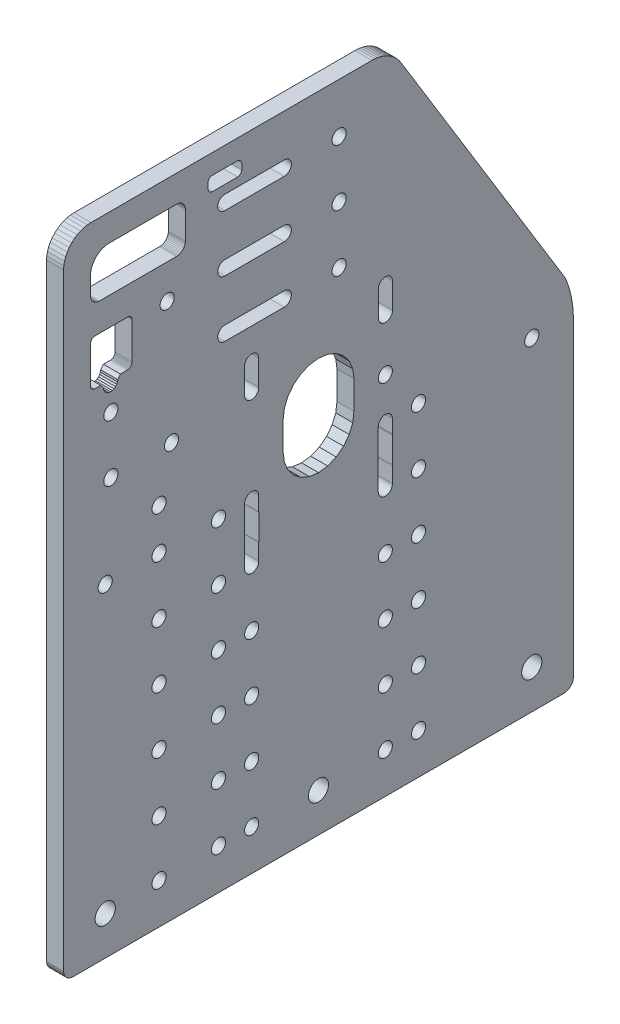
SolidWorks part; units mm, degrees
ref_plane "Front Plane" through (0, 0, 0) normal (0, 0, 1) x (1, 0, 0)
ref_plane "Top Plane" through (0, 0, 0) normal (0, 1, 0) x (1, 0, 0)
ref_plane "Right Plane" through (0, 0, 0) normal (1, 0, 0) x (0, 0, -1)
ref_plane "Plane1" through (0, 0, 0) normal (-1, 0, 0) x (0, -1, 0)
sketch "Sketch1" plane through (0, 0, 0) normal (-1, 0, 0) x (0, -1, 0)
  line L0 (-590.2121, -1614.2437) -> (-495.2304, -1672.3356)
  line L1 (-495.2304, -1672.3356) -> (-492.9855, -1673.1988)
  line L2 (-492.9855, -1673.1988) -> (-490.6881, -1673.9103)
  line L3 (-490.6881, -1673.9103) -> (-488.3483, -1674.4671)
  line L4 (-488.3483, -1674.4671) -> (-485.9766, -1674.8665)
  line L5 (-485.9766, -1674.8665) -> (-483.5835, -1675.1069)
  line L6 (-483.5835, -1675.1069) -> (-481.1798, -1675.1871)
  line L7 (-481.1798, -1675.1871) -> (-371.8266, -1675.1871)
  line L8 (-371.8266, -1675.1871) -> (-371.3877, -1675.1584)
  line L9 (-371.3877, -1675.1584) -> (-370.9562, -1675.0725)
  line L10 (-370.9562, -1675.0725) -> (-370.5397, -1674.9312)
  line L11 (-370.5397, -1674.9312) -> (-370.1452, -1674.7366)
  line L12 (-370.1452, -1674.7366) -> (-369.7795, -1674.4922)
  line L13 (-369.7795, -1674.4922) -> (-369.4487, -1674.2022)
  line L14 (-369.4487, -1674.2022) -> (-369.1587, -1673.8715)
  line L15 (-369.1587, -1673.8715) -> (-368.9143, -1673.5057)
  line L16 (-368.9143, -1673.5057) -> (-368.7198, -1673.1112)
  line L17 (-368.7198, -1673.1112) -> (-368.5784, -1672.6947)
  line L18 (-368.5784, -1672.6947) -> (-368.4926, -1672.2633)
  line L19 (-368.4926, -1672.2633) -> (-368.4638, -1671.8243)
  line L20 (-368.4638, -1671.8243) -> (-368.4638, -1498.5099)
  line L21 (-368.4638, -1498.5099) -> (-368.4926, -1498.071)
  line L22 (-368.4926, -1498.071) -> (-368.5784, -1497.6396)
  line L23 (-368.5784, -1497.6396) -> (-368.7198, -1497.223)
  line L24 (-368.7198, -1497.223) -> (-368.9143, -1496.8285)
  line L25 (-368.9143, -1496.8285) -> (-369.1587, -1496.4628)
  line L26 (-369.1587, -1496.4628) -> (-369.4487, -1496.1321)
  line L27 (-369.4487, -1496.1321) -> (-369.7795, -1495.842)
  line L28 (-369.7795, -1495.842) -> (-370.1452, -1495.5977)
  line L29 (-370.1452, -1495.5977) -> (-370.5397, -1495.4031)
  line L30 (-370.5397, -1495.4031) -> (-370.9562, -1495.2617)
  line L31 (-370.9562, -1495.2617) -> (-371.3877, -1495.1759)
  line L32 (-371.3877, -1495.1759) -> (-371.8266, -1495.1471)
  line L33 (-371.8266, -1495.1471) -> (-586.2881, -1495.1456)
  line L34 (-586.2881, -1495.1456) -> (-587.5497, -1495.2283)
  line L35 (-587.5497, -1495.2283) -> (-588.7897, -1495.475)
  line L36 (-588.7897, -1495.475) -> (-589.987, -1495.8813)
  line L37 (-589.987, -1495.8813) -> (-591.1209, -1496.4405)
  line L38 (-591.1209, -1496.4405) -> (-592.1721, -1497.1429)
  line L39 (-592.1721, -1497.1429) -> (-593.1227, -1497.9766)
  line L40 (-593.1227, -1497.9766) -> (-593.9563, -1498.9271)
  line L41 (-593.9563, -1498.9271) -> (-594.6588, -1499.9784)
  line L42 (-594.6588, -1499.9784) -> (-595.218, -1501.1123)
  line L43 (-595.218, -1501.1123) -> (-595.6244, -1502.3095)
  line L44 (-595.6244, -1502.3095) -> (-595.871, -1503.5495)
  line L45 (-595.871, -1503.5495) -> (-595.9537, -1504.8111)
  line L46 (-595.9537, -1504.8111) -> (-595.9537, -1603.9943)
  line L47 (-595.9537, -1603.9943) -> (-595.9102, -1605.016)
  line L48 (-595.9102, -1605.016) -> (-595.78, -1606.0302)
  line L49 (-595.78, -1606.0302) -> (-595.5641, -1607.0297)
  line L50 (-595.5641, -1607.0297) -> (-595.264, -1608.0073)
  line L51 (-595.264, -1608.0073) -> (-594.8819, -1608.9558)
  line L52 (-594.8819, -1608.9558) -> (-594.4205, -1609.8683)
  line L53 (-594.4205, -1609.8683) -> (-593.8833, -1610.7384)
  line L54 (-593.8833, -1610.7384) -> (-593.274, -1611.5596)
  line L55 (-593.274, -1611.5596) -> (-592.5971, -1612.3261)
  line L56 (-592.5971, -1612.3261) -> (-591.8575, -1613.0323)
  line L57 (-591.8575, -1613.0323) -> (-591.0606, -1613.673)
  line L58 (-591.0606, -1613.673) -> (-590.2121, -1614.2437)
  line L59 (-575.9778, -1552.0841) -> (-575.9778, -1573.0568)
  line L60 (-580.9777, -1573.098) -> (-580.9777, -1552.0841)
  line L61 (-535.9778, -1552.0854) -> (-535.9778, -1573.0582)
  line L62 (-540.9777, -1573.0993) -> (-540.9777, -1552.0854)
  line L63 (-555.9777, -1552.0992) -> (-555.9777, -1573.0855)
  line L64 (-560.9776, -1573.1131) -> (-560.9776, -1552.0992)
  line L65 (-524.9137, -1559.0552) -> (-515.9137, -1559.0552)
  line L66 (-515.9137, -1564.0552) -> (-524.9137, -1564.0552)
  line L67 (-524.9137, -1606.2991) -> (-515.9137, -1606.2991)
  line L68 (-515.9137, -1611.2991) -> (-524.9137, -1611.2991)
  line L69 (-477.6698, -1606.2991) -> (-468.6699, -1606.2991)
  line L70 (-468.6699, -1611.2991) -> (-477.6698, -1611.2991)
  line L71 (-477.6698, -1559.0528) -> (-468.6699, -1559.0552)
  line L72 (-468.6712, -1564.0782) -> (-477.6698, -1564.0758)
  line L73 (-586.0336, -1536.5791) -> (-586.215, -1536.2112)
  line L74 (-586.215, -1536.2112) -> (-586.3468, -1535.8228)
  line L75 (-586.3468, -1535.8228) -> (-586.4269, -1535.4204)
  line L76 (-586.4269, -1535.4204) -> (-586.4537, -1535.0111)
  line L77 (-586.4537, -1535.0111) -> (-586.4537, -1511.2962)
  line L78 (-586.4537, -1511.2962) -> (-586.3968, -1510.4284)
  line L79 (-586.3968, -1510.4284) -> (-586.2271, -1509.5753)
  line L80 (-586.2271, -1509.5753) -> (-585.9476, -1508.7517)
  line L81 (-585.9476, -1508.7517) -> (-585.5629, -1507.9717)
  line L82 (-585.5629, -1507.9717) -> (-585.0797, -1507.2485)
  line L83 (-585.0797, -1507.2485) -> (-584.5062, -1506.5946)
  line L84 (-584.5062, -1506.5946) -> (-583.8523, -1506.0211)
  line L85 (-583.8523, -1506.0211) -> (-583.1291, -1505.5379)
  line L86 (-583.1291, -1505.5379) -> (-582.3491, -1505.1533)
  line L87 (-582.3491, -1505.1533) -> (-581.5255, -1504.8737)
  line L88 (-581.5255, -1504.8737) -> (-580.6725, -1504.704)
  line L89 (-580.6725, -1504.704) -> (-579.8046, -1504.6471)
  line L90 (-579.8046, -1504.6471) -> (-573.6169, -1504.6471)
  line L91 (-573.6169, -1504.6471) -> (-573.2076, -1504.6739)
  line L92 (-573.2076, -1504.6739) -> (-572.8052, -1504.754)
  line L93 (-572.8052, -1504.754) -> (-572.4168, -1504.8858)
  line L94 (-572.4168, -1504.8858) -> (-572.0489, -1505.0673)
  line L95 (-572.0489, -1505.0673) -> (-571.7078, -1505.2952)
  line L96 (-571.7078, -1505.2952) -> (-571.3994, -1505.5656)
  line L97 (-571.3994, -1505.5656) -> (-571.1289, -1505.8741)
  line L98 (-571.1289, -1505.8741) -> (-570.901, -1506.2151)
  line L99 (-570.901, -1506.2151) -> (-570.7196, -1506.583)
  line L100 (-570.7196, -1506.583) -> (-570.5877, -1506.9715)
  line L101 (-570.5877, -1506.9715) -> (-570.5077, -1507.3738)
  line L102 (-570.5077, -1507.3738) -> (-570.4809, -1507.7831)
  line L103 (-570.4809, -1507.7831) -> (-570.4809, -1535.0111)
  line L104 (-570.4809, -1535.0111) -> (-570.5077, -1535.4204)
  line L105 (-570.5077, -1535.4204) -> (-570.5877, -1535.8228)
  line L106 (-570.5877, -1535.8228) -> (-570.7196, -1536.2112)
  line L107 (-570.7196, -1536.2112) -> (-570.901, -1536.5791)
  line L108 (-570.901, -1536.5791) -> (-571.1289, -1536.9202)
  line L109 (-571.1289, -1536.9202) -> (-571.3994, -1537.2286)
  line L110 (-571.3994, -1537.2286) -> (-571.7078, -1537.4991)
  line L111 (-571.7078, -1537.4991) -> (-572.0489, -1537.727)
  line L112 (-572.0489, -1537.727) -> (-572.4168, -1537.9084)
  line L113 (-572.4168, -1537.9084) -> (-572.8052, -1538.0403)
  line L114 (-572.8052, -1538.0403) -> (-573.2076, -1538.1203)
  line L115 (-573.2076, -1538.1203) -> (-573.6169, -1538.1471)
  line L116 (-573.6169, -1538.1471) -> (-583.3177, -1538.1471)
  line L117 (-583.3177, -1538.1471) -> (-583.727, -1538.1203)
  line L118 (-583.727, -1538.1203) -> (-584.1293, -1538.0403)
  line L119 (-584.1293, -1538.0403) -> (-584.5178, -1537.9084)
  line L120 (-584.5178, -1537.9084) -> (-584.8857, -1537.727)
  line L121 (-584.8857, -1537.727) -> (-585.2268, -1537.4991)
  line L122 (-585.2268, -1537.4991) -> (-585.5352, -1537.2286)
  line L123 (-585.5352, -1537.2286) -> (-585.8057, -1536.9202)
  line L124 (-585.8057, -1536.9202) -> (-586.0336, -1536.5791)
  line L125 (-560.5397, -1505.8783) -> (-560.4696, -1505.6715)
  line L126 (-560.4696, -1505.6715) -> (-560.373, -1505.4757)
  line L127 (-560.373, -1505.4757) -> (-560.2517, -1505.2942)
  line L128 (-560.2517, -1505.2942) -> (-560.1078, -1505.1301)
  line L129 (-560.1078, -1505.1301) -> (-559.9436, -1504.9862)
  line L130 (-559.9436, -1504.9862) -> (-559.7621, -1504.8649)
  line L131 (-559.7621, -1504.8649) -> (-559.5663, -1504.7683)
  line L132 (-559.5663, -1504.7683) -> (-559.3596, -1504.6981)
  line L133 (-559.3596, -1504.6981) -> (-559.1312, -1504.6471)
  line L134 (-559.1312, -1504.6471) -> (-558.9276, -1504.6413)
  line L135 (-558.9276, -1504.6413) -> (-548.4809, -1504.6452)
  line L136 (-548.4809, -1504.6452) -> (-545.8818, -1504.6452)
  line L137 (-545.8818, -1504.6452) -> (-545.6677, -1504.6877)
  line L138 (-545.6677, -1504.6877) -> (-545.461, -1504.7579)
  line L139 (-545.461, -1504.7579) -> (-545.2652, -1504.8545)
  line L140 (-545.2652, -1504.8545) -> (-545.0837, -1504.9758)
  line L141 (-545.0837, -1504.9758) -> (-544.9196, -1505.1197)
  line L142 (-544.9196, -1505.1197) -> (-544.7756, -1505.2838)
  line L143 (-544.7756, -1505.2838) -> (-544.6543, -1505.4654)
  line L144 (-544.6543, -1505.4654) -> (-544.5578, -1505.6612)
  line L145 (-544.5578, -1505.6612) -> (-544.4876, -1505.8679)
  line L146 (-544.4876, -1505.8679) -> (-544.445, -1506.082)
  line L147 (-544.445, -1506.082) -> (-544.4414, -1508.2677)
  line L148 (-544.4414, -1508.2677) -> (-543.221, -1509.2377)
  line L149 (-543.221, -1509.2377) -> (-542.574, -1509.3226)
  line L150 (-542.574, -1509.3226) -> (-541.9709, -1509.5721)
  line L151 (-541.9709, -1509.5721) -> (-541.453, -1509.9692)
  line L152 (-541.453, -1509.9692) -> (-541.0555, -1510.4868)
  line L153 (-541.0555, -1510.4868) -> (-540.8055, -1511.0897)
  line L154 (-540.8055, -1511.0897) -> (-540.72, -1511.7367)
  line L155 (-540.72, -1511.7367) -> (-540.805, -1512.3838)
  line L156 (-540.805, -1512.3838) -> (-541.0545, -1512.9868)
  line L157 (-541.0545, -1512.9868) -> (-541.4516, -1513.5047)
  line L158 (-541.4516, -1513.5047) -> (-541.9692, -1513.9022)
  line L159 (-541.9692, -1513.9022) -> (-542.572, -1514.1522)
  line L160 (-542.572, -1514.1522) -> (-543.219, -1514.2377)
  line L161 (-543.219, -1514.2377) -> (-544.4323, -1515.2077)
  line L162 (-544.4323, -1515.2077) -> (-544.4307, -1517.6776)
  line L163 (-544.4307, -1517.6776) -> (-544.4876, -1518.1096)
  line L164 (-544.4876, -1518.1096) -> (-544.5578, -1518.3163)
  line L165 (-544.5578, -1518.3163) -> (-544.6543, -1518.5121)
  line L166 (-544.6543, -1518.5121) -> (-544.7756, -1518.6936)
  line L167 (-544.7756, -1518.6936) -> (-544.9196, -1518.8578)
  line L168 (-544.9196, -1518.8578) -> (-545.0837, -1519.0017)
  line L169 (-545.0837, -1519.0017) -> (-545.2652, -1519.123)
  line L170 (-545.2652, -1519.123) -> (-545.461, -1519.2196)
  line L171 (-545.461, -1519.2196) -> (-545.6677, -1519.2897)
  line L172 (-545.6677, -1519.2897) -> (-546.0997, -1519.3486)
  line L173 (-546.0997, -1519.3486) -> (-558.9578, -1519.3427)
  line L174 (-558.9578, -1519.3427) -> (-559.1455, -1519.3427)
  line L175 (-559.1455, -1519.3427) -> (-559.3596, -1519.3001)
  line L176 (-559.3596, -1519.3001) -> (-559.5663, -1519.23)
  line L177 (-559.5663, -1519.23) -> (-559.7621, -1519.1334)
  line L178 (-559.7621, -1519.1334) -> (-559.9436, -1519.0121)
  line L179 (-559.9436, -1519.0121) -> (-560.1078, -1518.8682)
  line L180 (-560.1078, -1518.8682) -> (-560.2517, -1518.704)
  line L181 (-560.2517, -1518.704) -> (-560.373, -1518.5225)
  line L182 (-560.373, -1518.5225) -> (-560.4696, -1518.3267)
  line L183 (-560.4696, -1518.3267) -> (-560.5397, -1518.12)
  line L184 (-560.5397, -1518.12) -> (-560.5823, -1517.9059)
  line L185 (-560.5823, -1517.9059) -> (-560.5823, -1517.6796)
  line L186 (-560.5823, -1517.6796) -> (-560.568, -1506.084)
  line L187 (-560.568, -1506.084) -> (-560.5397, -1505.8783)
  line L188 (-512.6093, -1578.9371) -> (-510.6228, -1576.3483)
  line L189 (-510.6228, -1576.3483) -> (-508.034, -1574.3618)
  line L190 (-508.034, -1574.3618) -> (-505.0192, -1573.1131)
  line L191 (-505.0192, -1573.1131) -> (-501.784, -1572.6871)
  line L192 (-501.784, -1572.6871) -> (-491.784, -1572.6871)
  line L193 (-491.784, -1572.6871) -> (-488.5487, -1573.1131)
  line L194 (-488.5487, -1573.1131) -> (-485.534, -1574.3618)
  line L195 (-485.534, -1574.3618) -> (-482.9451, -1576.3483)
  line L196 (-482.9451, -1576.3483) -> (-480.9587, -1578.9371)
  line L197 (-480.9587, -1578.9371) -> (-479.7099, -1581.9519)
  line L198 (-479.7099, -1581.9519) -> (-479.284, -1585.1871)
  line L199 (-479.284, -1585.1871) -> (-479.7099, -1588.4224)
  line L200 (-479.7099, -1588.4224) -> (-480.9587, -1591.4371)
  line L201 (-480.9587, -1591.4371) -> (-482.9451, -1594.026)
  line L202 (-482.9451, -1594.026) -> (-485.534, -1596.0125)
  line L203 (-485.534, -1596.0125) -> (-488.5487, -1597.2612)
  line L204 (-488.5487, -1597.2612) -> (-491.784, -1597.6871)
  line L205 (-491.784, -1597.6871) -> (-501.784, -1597.6871)
  line L206 (-501.784, -1597.6871) -> (-505.0192, -1597.2612)
  line L207 (-505.0192, -1597.2612) -> (-508.034, -1596.0125)
  line L208 (-508.034, -1596.0125) -> (-510.6228, -1594.026)
  line L209 (-510.6228, -1594.026) -> (-512.6093, -1591.4371)
  line L210 (-512.6093, -1591.4371) -> (-513.858, -1588.4224)
  line L211 (-513.858, -1588.4224) -> (-514.284, -1585.1871)
  line L212 (-514.284, -1585.1871) -> (-513.858, -1581.9519)
  line L213 (-513.858, -1581.9519) -> (-512.6093, -1578.9371)
  line L214 (-588.9809, -1556.6482) -> (-588.9809, -1547.5504)
  line L215 (-587.544, -1546.1136) -> (-585.6436, -1546.0993)
  line L216 (-583.9746, -1547.7683) -> (-583.9889, -1556.6482)
  line L217 (-585.4257, -1558.085) -> (-587.544, -1558.085)
  arc A0 (-580.9777, -1552.0841) -> (-575.9778, -1552.0841) centre (-578.4777, -1552.0704) cw
  arc A1 (-575.9778, -1573.0568) -> (-580.9777, -1573.098) centre (-578.4777, -1573.0774) cw
  arc A2 (-540.9777, -1552.0854) -> (-535.9778, -1552.0854) centre (-538.4778, -1552.0718) cw
  arc A3 (-535.9778, -1573.0582) -> (-540.9777, -1573.0993) centre (-538.4778, -1573.0787) cw
  arc A4 (-560.9776, -1552.0992) -> (-555.9777, -1552.0992) centre (-558.4777, -1552.0856) cw
  arc A5 (-555.9777, -1573.0855) -> (-560.9776, -1573.1131) centre (-558.4777, -1573.0993) cw
  arc A6 (-515.9137, -1559.0552) -> (-515.9137, -1564.0552) centre (-515.9137, -1561.5552) cw
  arc A7 (-524.9137, -1564.0552) -> (-524.9137, -1559.0552) centre (-524.9137, -1561.5552) cw
  arc A8 (-515.9137, -1606.2991) -> (-515.9137, -1611.2991) centre (-515.9137, -1608.7991) cw
  arc A9 (-524.9137, -1611.2991) -> (-524.9137, -1606.2991) centre (-524.9137, -1608.7991) cw
  arc A10 (-468.6699, -1606.2991) -> (-468.6699, -1611.2991) centre (-468.6699, -1608.7991) cw
  arc A11 (-477.6698, -1611.2991) -> (-477.6698, -1606.2991) centre (-477.6698, -1608.7991) cw
  arc A12 (-468.6699, -1559.0552) -> (-468.6712, -1564.0782) centre (-468.6705, -1561.5667) cw
  arc A13 (-477.6698, -1564.0758) -> (-477.6698, -1559.0528) centre (-477.6692, -1561.5643) cw
  circle A14 centre (-382.1591, -1509.8471) radius 3.5685
  circle A15 centre (-382.1591, -1585.1671) radius 3.5685
  circle A16 centre (-382.1591, -1660.4871) radius 3.5685
  circle A17 centre (-538.3993, -1592.4578) radius 2.5
  circle A18 centre (-558.4485, -1592.4578) radius 2.5
  circle A19 centre (-578.4485, -1592.4578) radius 2.5
  circle A20 centre (-534.4436, -1511.8471) radius 2.5
  circle A21 centre (-558.4024, -1531.723) radius 2.5
  circle A22 centre (-514.4436, -1511.8471) radius 2.5
  circle A23 centre (-514.4436, -1533.239) radius 2.5
  circle A24 centre (-497.4962, -1528.8471) radius 2.5
  circle A25 centre (-482.7991, -1549.8471) radius 2.5
  circle A26 centre (-482.7991, -1509.8471) radius 2.5
  circle A27 centre (-482.7991, -1620.4871) radius 2.5
  circle A28 centre (-482.7991, -1660.4871) radius 2.5
  circle A29 centre (-402.4962, -1528.8471) radius 2.5
  arc A30 (-588.9809, -1547.5504) -> (-587.544, -1546.1136) centre (-587.3137, -1547.7807) cw
  arc A31 (-585.6436, -1546.0993) -> (-583.9746, -1547.7683) centre (-585.6436, -1547.7683) cw
  arc A32 (-583.9889, -1556.6482) -> (-585.4257, -1558.085) centre (-585.656, -1556.4179) cw
  arc A33 (-587.544, -1558.085) -> (-588.9809, -1556.6482) centre (-587.3262, -1556.4303) cw
extrude "Boss-Extrude1" add sketch "Sketch1" against normal blind 6
sketch "Sketch2" plane through (6, 0, 0) normal (1, 0, 0) x (0, 0, -1)
  line L0 (1561.5671, 482.7991) -> (1561.5671, 462.7991) construction
  line L1 (1564.0671, 482.7991) -> (1564.0671, 462.7991)
  line L2 (1559.0671, 482.7991) -> (1559.0671, 462.7991)
  line L3 (1608.7671, 482.7991) -> (1608.7671, 462.7991) construction
  line L4 (1611.2671, 482.7991) -> (1611.2671, 462.7991)
  line L5 (1606.2671, 482.7991) -> (1606.2671, 462.7991)
  circle A0 centre (1608.7671, 442.7991) radius 2.5
  circle A26 centre (1620.4871, 402.7991) radius 2.5
  circle A27 centre (1620.4871, 482.7991) radius 2.5 construction
  circle A28 centre (1549.8471, 482.7991) radius 2.5 construction
  circle A29 centre (1620.4871, 482.7991) radius 2.5
  circle A30 centre (1549.8471, 482.7991) radius 2.5
  arc A32 (1564.0671, 482.7991) -> (1559.0671, 482.7991) centre (1561.5671, 482.7991) ccw
  circle A35 centre (1549.8471, 462.7991) radius 2.5
  circle A36 centre (1620.4871, 462.7991) radius 2.5
  circle A39 centre (1549.8471, 442.7991) radius 2.5
  circle A40 centre (1620.4871, 442.7991) radius 2.5
  circle A43 centre (1549.8471, 422.7991) radius 2.5
  circle A44 centre (1620.4871, 422.7991) radius 2.5
  circle A47 centre (1549.8471, 402.7991) radius 2.5
  circle A49 centre (1549.8471, 382.7991) radius 2.5
  circle A51 centre (1620.4871, 382.7991) radius 2.5
  circle A52 centre (1608.7671, 422.7991) radius 2.5
  circle A53 centre (1608.7671, 382.7991) radius 2.5
  arc A54 (1559.0671, 462.7991) -> (1564.0671, 462.7991) centre (1561.5671, 462.7991) ccw
  circle A55 centre (1561.5671, 442.7991) radius 2.5
  circle A56 centre (1561.5671, 422.7991) radius 2.5
  circle A57 centre (1561.5671, 402.7991) radius 2.5
  circle A58 centre (1561.5671, 382.7991) radius 2.5
  circle A61 centre (1608.7671, 402.7991) radius 2.5
  arc A62 (1611.2671, 482.7991) -> (1606.2671, 482.7991) centre (1608.7671, 482.7991) ccw
  arc A63 (1606.2671, 462.7991) -> (1611.2671, 462.7991) centre (1608.7671, 462.7991) ccw
  arc A64 (1611.2671, 482.7991) -> (1606.2671, 482.7991) centre (1608.7671, 482.7991) ccw
  arc A65 (1606.2671, 462.7991) -> (1611.2671, 462.7991) centre (1608.7671, 462.7991) ccw
  circle A66 centre (1528.8471, 497.4962) radius 2.5 construction
  circle A67 centre (1528.8471, 497.4962) radius 2.5
  circle A68 centre (1608.7671, 497.4962) radius 2.5
  circle A69 centre (1528.8471, 482.7962) radius 2.5
  circle A70 centre (1528.8471, 462.7861) radius 2.5
  circle A71 centre (1528.8471, 442.7761) radius 2.5
  circle A72 centre (1528.8471, 422.766) radius 2.5
  circle A74 centre (1528.8471, 382.7459) radius 2.5
  circle A75 centre (1528.8471, 402.756) radius 2.5 [skipped]
  point P19 (1608.7671, 472.7991)
  point P54 (1561.5671, 472.7991)
  dimension "D2" = 6
  dimension "D4" = 79.92
  dimension "D6" = 3
  dimension "D7" = 2
  dimension "D9" = 2
  dimension "D10" = 14.7
  dimension "D11" = 6
  dimension "D12" = 2
  dimension "D15" = 2
  dimension "D3" = 2
  dimension "D5" = 4
  dimension "D8" = 2
extrude "Cut-Extrude3" cut sketch "Sketch2" against normal through all contours L5 A63 L4 A62 | A39 | A30 | A35 | A43 | A47 | A49 | A58 | A57 | A56 | A55 | L1 A54 L2 A32 | A36 | A61 | A53 | A51 | A26 | A44 | A52 | A0 | A40 | A29 | A68 | A74 | A70 | A71 | A69 | A72
